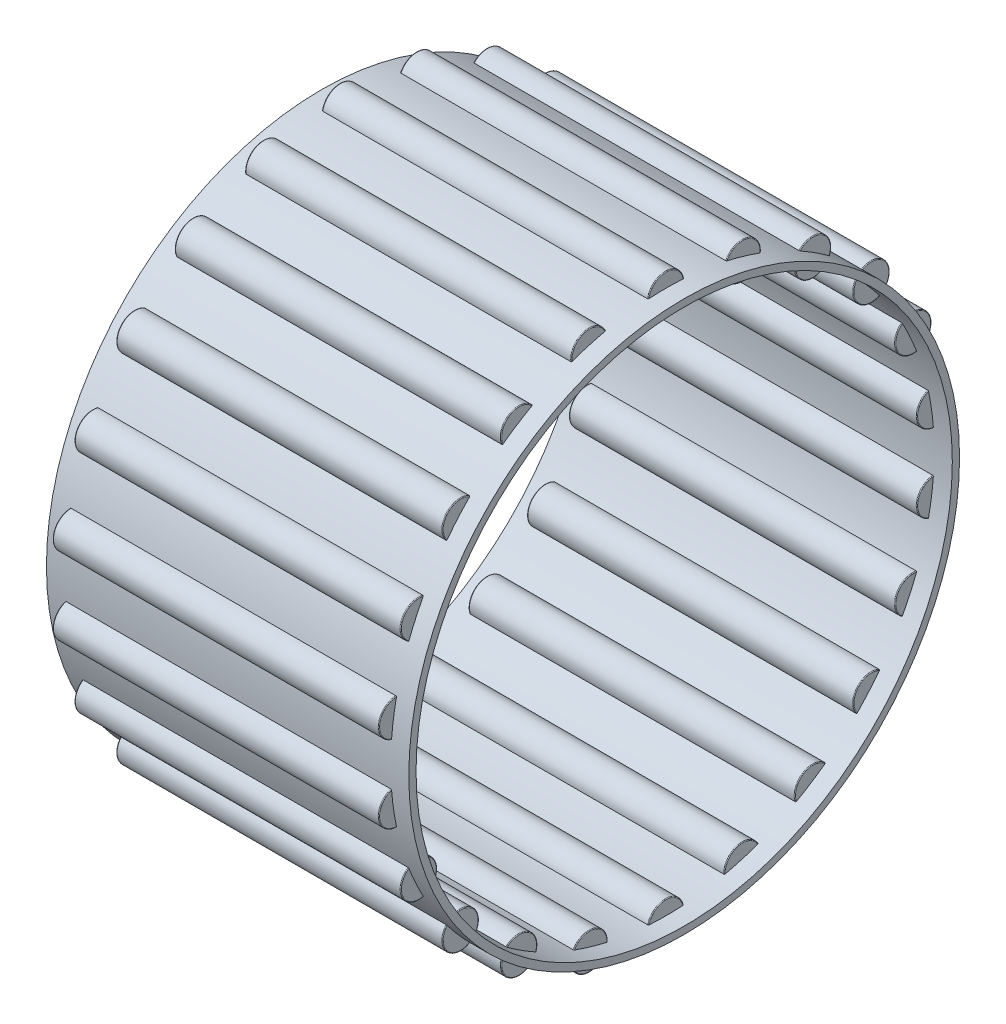
SolidWorks part; units mm, degrees
ref_plane "Plane1" through (0, 0, 0) normal (0, 0, 1) x (1, 0, 0)
ref_plane "Plane2" through (0, 0, 0) normal (0, 1, 0) x (1, 0, 0)
ref_plane "Plane3" through (0, 0, 0) normal (1, 0, 0) x (0, 0, -1)
sketch "Clipboard" plane through (0, 0, 0) normal (0, 0, 1) x (1, 0, 0)
  line L0 (-10, 0) -> (10, 0) construction
  line L1 (0, 0) -> (20.7325, -8.3765)
  line L2 (0, 0) -> (47.1009, 19.03)
  line L3 (0, 0) -> (23.8125, -9.6209)
  line L4 (0, 0) -> (-44.45, -1.5522)
  dimension "OD" = 50.8
  dimension "Count" = 22
  dimension "Show_count" = 22
  dimension "Max_count" = 22
  dimension "Min_count" = 2
  dimension "RollCLRad" = 23.8125
  dimension "Bore" = 44.45
sketch "CagSpiSke" plane through (0, 0, 0) normal (0, 0, 1) x (1, 0, 0)
  line L0 (15.875, 23.495) -> (15.875, 24.13)
  line L1 (15.875, 24.13) -> (-15.875, 24.13)
  line L2 (-15.875, 24.13) -> (-15.875, 23.495)
  line L3 (-15.875, 23.495) -> (15.875, 23.495)
  line L4 (-12.7, 0) -> (12.7, 0) construction
  dimension "cagRadius" = 23.495
  dimension "thickness" = 0.635
  dimension "Width" = 31.75
  dimension "halfWidth" = 15.875
revolve "CageSpine" add sketch "CagSpiSke" angle 360 about L4
sketch "RolDetSke" plane through (0, 0, 0) normal (0, 0, 1) x (1, 0, 0)
  line L0 (-17.78, 23.8125) -> (17.78, 23.8125) construction
  line L2 (-14.224, 25.4) -> (14.224, 25.4)
  line L3 (-14.2875, 25.3365) -> (-14.2875, 23.8125)
  line L5 (-14.2875, 23.8125) -> (14.2875, 23.8125)
  line L6 (14.2875, 25.3365) -> (14.2875, 23.8125)
  arc A0 (-14.224, 25.4) -> (-14.2875, 25.3365) centre (-14.224, 25.3365) ccw
  arc A1 (14.2875, 25.3365) -> (14.224, 25.4) centre (14.224, 25.3365) ccw
  dimension "radius" = 0.0635
  dimension "CLRad" = 23.8125
  dimension "Cyl_Len" = 28.575
  dimension "halfCylLen" = 14.2875
  dimension "Roller_diameter" = 3.175
revolve "RollerDetailed" add sketch "RolDetSke" angle 360 about L0
ref_axis "Axis1" through (-50, 0, 0) along (1, 0, 0)
pattern_circular "RollersDetailed" count 22 every 16.364 about axis through (-50, 0, 0) along (1, 0, 0) of "RollerDetailed"
sketch "RolSimSke" plane through (0, 0, 0) normal (0, 0, 1) x (1, 0, 0)
  line L0 (-17.78, 0) -> (17.78, 0) construction
  line L1 (-12.7, 0) -> (-38.1, 0) construction
  line L3 (-14.224, 25.4) -> (14.224, 25.4)
  line L4 (-14.2875, 25.3365) -> (-14.2875, 22.2885)
  line L5 (-14.224, 22.225) -> (14.224, 22.225)
  line L6 (14.2875, 25.3365) -> (14.2875, 22.2885)
  arc A0 (14.2875, 22.2885) -> (14.224, 22.225) centre (14.224, 22.2885) cw
  arc A1 (14.224, 25.4) -> (14.2875, 25.3365) centre (14.224, 25.3365) cw
  arc A2 (-14.2875, 25.3365) -> (-14.224, 25.4) centre (-14.224, 25.3365) cw
  arc A3 (-14.224, 22.225) -> (-14.2875, 22.2885) centre (-14.224, 22.2885) cw
  point P13 (14.2875, 25.4)
  point P16 (-14.2875, 25.4)
  point P19 (-14.2875, 22.225)
  dimension "Bore" = 44.45
  dimension "radius" = 0.0635
  dimension "Cyl_Len" = 28.575
  dimension "Roller_diameter" = 3.175
  dimension "D1" = 14.2875
revolve "RollersSimplified" [suppressed] add sketch "RolSimSke" angle 360 about L0
equation "\"RollCLRad@Clipboard\" = ( \"OD@Clipboard\" + \"Bore@Clipboard\" )  / 4"
equation "\"CLRad@RolDetSke\" = \"RollCLRad@Clipboard\""
equation "\"thickness@CagSpiSke\"  = ( \"OD@Clipboard\" - \"Bore@Clipboard\" )  / 10"
equation "\"cagRadius@CagSpiSke\" =  \"RollCLRad@Clipboard\" -  ( \"thickness@CagSpiSke\" / 2 ) "
equation "\"halfWidth@CagSpiSke\" = \"Width@CagSpiSke\" / 2"
equation "\"Bore@RolSimSke\" = \"Bore@Clipboard\""
equation "\"Roller_diameter@RolDetSke\" =  ( \"OD@Clipboard\" - \"Bore@Clipboard\" )  / 2"
equation "\"halfCylLen@RolDetSke\" = \"Cyl_Len@RolDetSke\" / 2"
equation "\"radius@RolDetSke\" = \"Roller_diameter@RolDetSke\" / 50"
equation "\"Cyl_Len@RolSimSke\" = \"Cyl_Len@RolDetSke\""
equation "\"D1@RolSimSke\" = \"Cyl_Len@RolSimSke\"/2"
equation "\"radius@RolSimSke\" = \"radius@RolDetSke\""
equation "\"Roller_diameter@RolSimSke\" =  ( \"OD@Clipboard\" - \"Bore@Clipboard\" )  / 2"
equation "\"Max_count@Clipboard\" = int( 3.14159265 / atn(( \"Roller_diameter@RolDetSke\" / 2) / sqr(\"RollCLRad@Clipboard\"  * \"RollCLRad@Clipboard\" - ( \"Roller_diameter@RolDetSke\" / 2) *  ( \"Roller_diameter@RolDetSke\" / 2))))"
equation "\"Max_count@Clipboard\" = ((sgn( \"Max_count@Clipboard\" - \"Count@Clipboard\" )-1)*( \"Max_count@Clipboard\" - \"Count@Clipboard\" ))/-2+ \"Count@Clipboard\""
equation "\"Count@RollersDetailed\" = int( \"Show_count@Clipboard\" ) "
equation "\"Count@RollersDetailed\" = ((sgn( \"Count@RollersDetailed\" - \"Max_count@Clipboard\" )-1)*( \"Count@RollersDetailed\" - \"Max_count@Clipboard\" ))/-2+ \"Max_count@Clipboard\""
equation "\"Count@RollersDetailed\" = ((sgn( \"Count@RollersDetailed\" - \"Min_count@Clipboard\" )+1)*( \"Count@RollersDetailed\" - \"Min_count@Clipboard\"))/2 +\"Min_count@Clipboard\""
equation "\"Angle@RollersDetailed\" = 360.0 / \"Max_count@Clipboard\""
